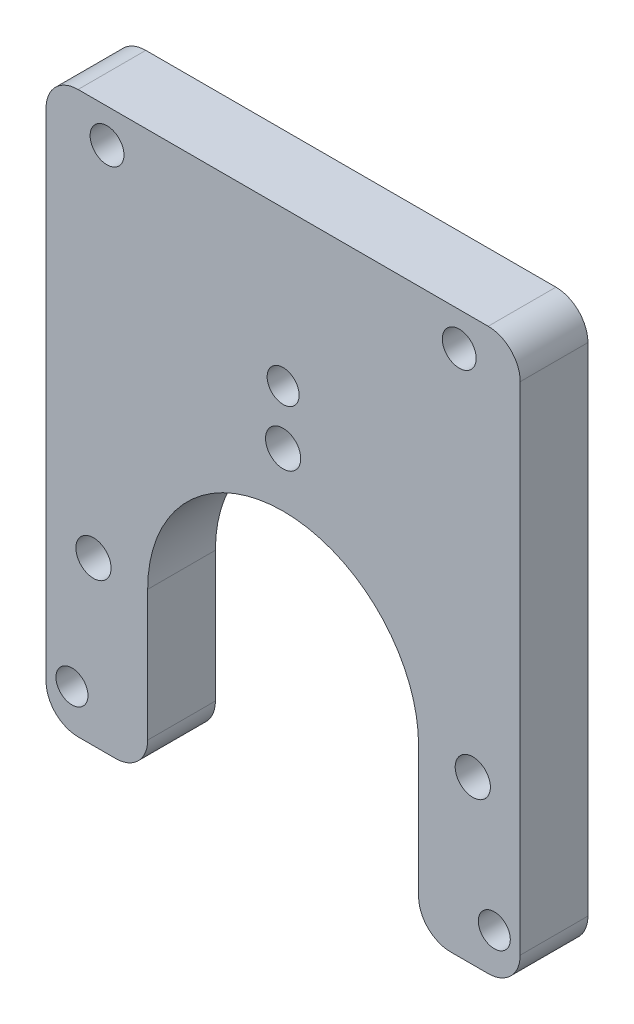
SolidWorks part; units mm, degrees
material "Acrylic (Medium-high impact)"
ref_plane "Front Plane" through (0, 0, 0) normal (0, 0, 1) x (1, 0, 0)
ref_plane "Top Plane" through (0, 0, 0) normal (0, 1, 0) x (1, 0, 0)
ref_plane "Right Plane" through (0, 0, 0) normal (1, 0, 0) x (0, 0, -1)
sketch "Sketch1" plane through (0, 0, 0) normal (0, 0, 1) x (1, 0, 0)
  line L0 (22.225, -22.083) -> (22.225, 52.563) construction
  line L1 (0, 0) -> (9.525, 0)
  line L2 (0, 0) -> (0, 52.563)
  line L3 (0, 52.563) -> (44.45, 52.563)
  line L4 (44.45, 0) -> (44.45, 52.563)
  line L5 (0, 15.24) -> (44.45, 15.24) construction
  line L6 (5.715, 52.563) -> (5.715, 49.388) construction
  line L8 (22.225, 27.94) -> (22.225, 38.1) construction
  line L9 (22.225, 38.1) -> (22.225, 27.94) construction
  line L10 (9.525, 15.24) -> (9.525, 0)
  line L11 (34.925, 15.24) -> (34.925, 0)
  line L12 (34.925, 0) -> (44.45, 0)
  line L13 (2.4277, 3.81) -> (22.225, 15.24) construction
  line L14 (22.225, 15.24) -> (42.0223, 3.81) construction
  circle A0 centre (5.715, 49.388) radius 1.5875
  circle A1 centre (38.735, 49.388) radius 1.5875
  circle A2 centre (4.445, 15.24) radius 1.65
  circle A3 centre (22.225, 33.02) radius 1.65
  circle A4 centre (40.005, 15.24) radius 1.65
  arc A8 (34.925, 15.24) -> (9.525, 15.24) centre (22.225, 15.24) ccw
  circle A9 centre (22.225, 38.1) radius 1.5
  circle A10 centre (42.0223, 3.81) radius 1.5
  circle A11 centre (2.4277, 3.81) radius 1.5
  circle A12 centre (22.225, 15.24) radius 22.86 construction
  point P9 (5.715, 52.563)
  point P23 (22.225, 15.24)
  point P39 (22.225, 15.24)
  dimension "D5" = 3.175
  dimension "D6" = 25.4
  dimension "D7" = 3
  dimension "D11" = 3.3
  dimension "D13" = 17.78
  dimension "D1" = 44.45
  dimension "D2" = 15.24
  dimension "D3" = 16.51
  dimension "D4" = 3.175
  dimension "D8" = 10.16
  dimension "D10" = 37.323
  dimension "D9" = 3
  dimension "D12" = 3
extrude "Boss-Extrude1" add sketch "Sketch1" along normal blind 6.35
fillet "Fillet1" radius 3 6 edges at (0, 52.563, 3.175) (44.45, 52.563, 3.175) (44.45, 0, 3.175) (34.925, 0, 3.175) (9.525, 0, 3.175) (0, 0, 3.175)
